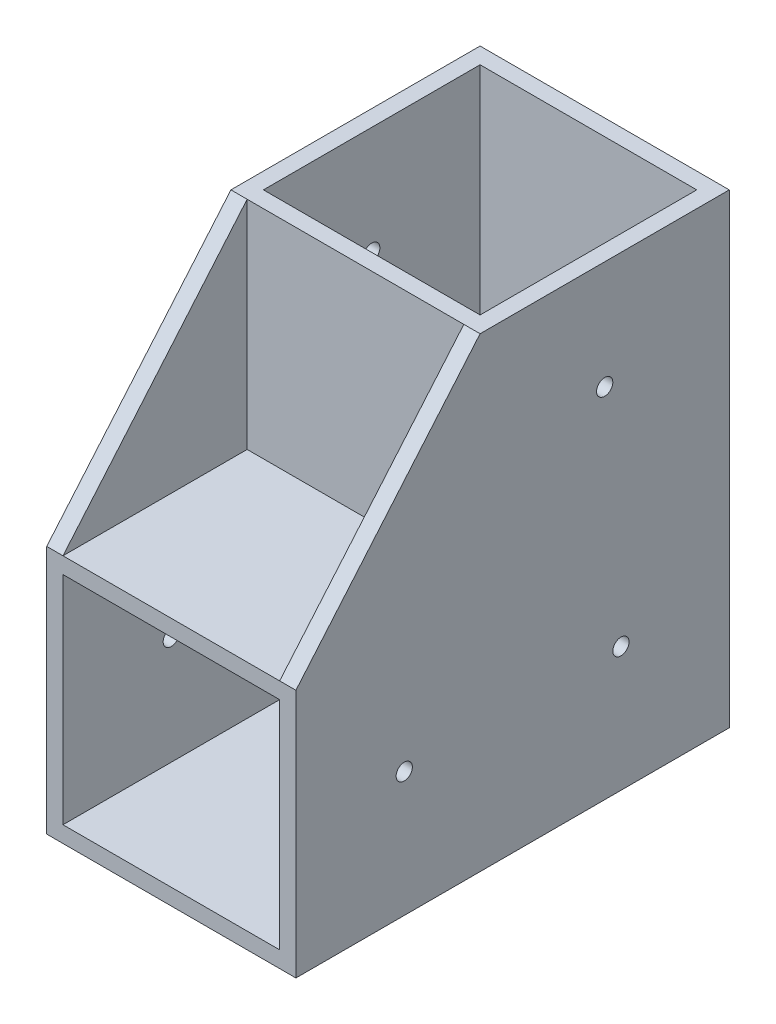
SolidWorks part; units mm, degrees
material "PA Type 6"
ref_plane "Front Plane" through (0, 0, 0) normal (0, 0, 1) x (1, 0, 0)
ref_plane "Top Plane" through (0, 0, 0) normal (0, 1, 0) x (1, 0, 0)
ref_plane "Right Plane" through (0, 0, 0) normal (1, 0, 0) x (0, 0, -1)
sketch "Esquisse1" plane through (0, 0, 0) normal (0, 0, 1) x (1, 0, 0)
  line L1 (0, 0) -> (46, 0)
  line L2 (0, 0) -> (0, -46)
  line L3 (0, -46) -> (46, -46)
  line L4 (46, 0) -> (46, -46)
  line L5 (3, -3) -> (43, -3)
  line L6 (3, -3) -> (3, -43)
  line L7 (3, -43) -> (43, -43)
  line L8 (43, -3) -> (43, -43)
  dimension "D1" = 40
  dimension "D2" = 3
  dimension "D3" = 3
  dimension "D4" = 3
extrude "Boss.-Extru.1" add sketch "Esquisse1" along normal blind 80
sketch "Esquisse2" plane through (0, 0, 0) normal (0, 1, 0) x (1, 0, 0)
  line L0 (46, -80) -> (46, 0) construction
  line L1 (0, 0) -> (46, 0)
  line L2 (0, 0) -> (0, -46)
  line L3 (0, -46) -> (46, -46)
  line L4 (46, 0) -> (46, -46)
  line L5 (3, -80) -> (3, 0) construction
  line L6 (3, -3) -> (43, -3)
  line L7 (3, -3) -> (3, -43)
  line L8 (3, -43) -> (43, -43)
  line L9 (43, -3) -> (43, -43)
  dimension "D1" = 40
  dimension "D2" = 3
extrude "Boss.-Extru.2" add sketch "Esquisse2" along normal blind 40
sketch "Esquisse3" plane through (46, 0, 0) normal (1, 0, 0) x (0, 0, -1)
  line L0 (-80, 0) -> (-46, 40)
  line L1 (-46, 40) -> (-46, 0)
  line L2 (-46, 0) -> (-80, 0)
extrude "Boss.-Extru.3" add sketch "Esquisse3" against normal blind 3
sketch "Esquisse4" plane through (0, 0, 0) normal (-1, 0, 0) x (0, 0, 1)
  line L0 (46, 40) -> (80, 0)
  line L1 (0, 40) -> (46, 40) construction
  line L2 (46, 0) -> (46, 40) construction
  line L3 (80, 0) -> (46, 0)
  line L4 (80, 0) -> (46, 0) construction
  line L5 (80, 0) -> (46, 0) construction
  line L6 (46, 0) -> (46, 40)
extrude "Boss.-Extru.4" add sketch "Esquisse4" against normal blind 3
sketch "Esquisse5" plane through (0, 0, 0) normal (-1, 0, 0) x (0, 0, 1)
  line L0 (20, -23) -> (60, -23) construction
  line L1 (40, -23) -> (40, -46) construction
  line L2 (80, -46) -> (0, -46) construction
  line L3 (3, 40) -> (43, 0) construction
  circle A0 centre (23, 20) radius 1.5
  circle A1 centre (20, -23) radius 1.5
  circle A2 centre (60, -23) radius 1.5
  dimension "D1" = 3
  dimension "D2" = 23
  dimension "D3" = 40
extrude "Enlèv. mat.-Extru.1" cut sketch "Esquisse5" against normal through all
